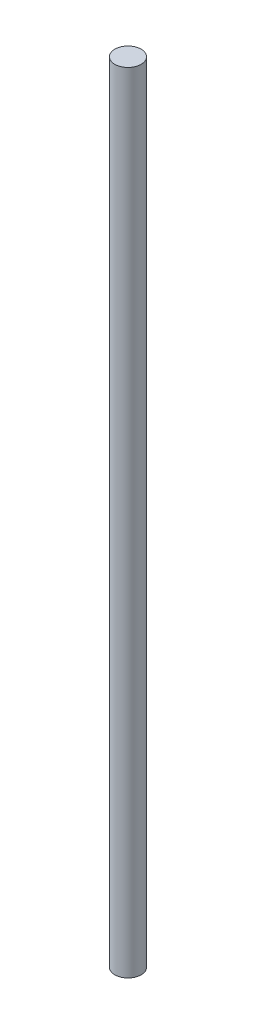
SolidWorks part; units mm, degrees
ref_plane "前视基准面" through (0, 0, 0) normal (0, 0, 1) x (1, 0, 0)
ref_plane "上视基准面" through (0, 0, 0) normal (0, 1, 0) x (1, 0, 0)
ref_plane "右视基准面" through (0, 0, 0) normal (1, 0, 0) x (0, 0, -1)
other "Configuration Table"
sketch "草图1" plane through (0, 0, 0) normal (0, 1, 0) x (1, 0, 0)
  circle A0 centre (0, 0) radius 1
  dimension "D1" = 2
extrude "凸台-拉伸1" add sketch "草图1" along normal blind 60
